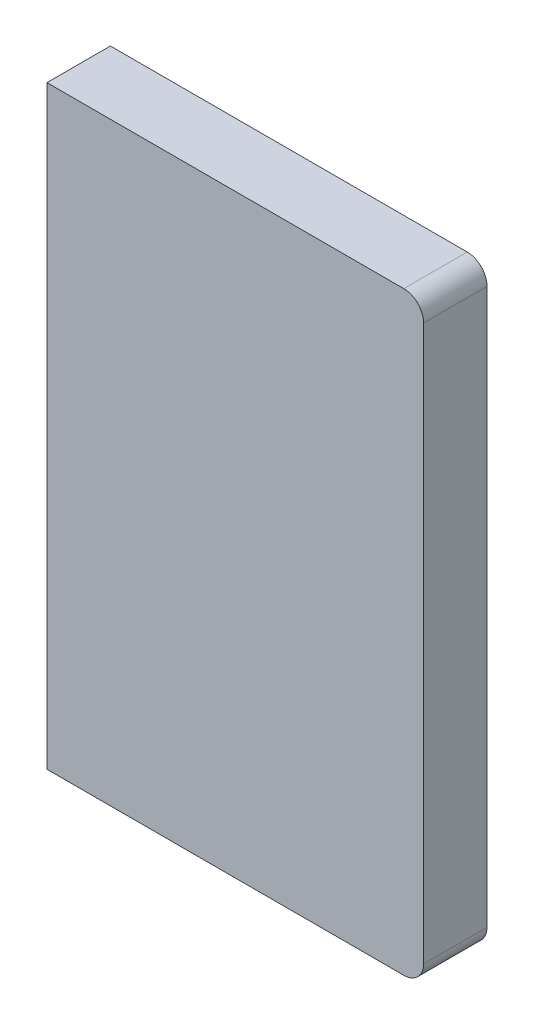
SolidWorks part; units mm, degrees
ref_plane "Front Plane" through (0, 0, 0) normal (0, 0, 1) x (1, 0, 0)
ref_plane "Top Plane" through (0, 0, 0) normal (0, 1, 0) x (1, 0, 0)
ref_plane "Right Plane" through (0, 0, 0) normal (1, 0, 0) x (0, 0, -1)
sketch "Sketch1" plane through (0, 0, 0) normal (0, 0, 1) x (1, 0, 0)
  line L1 (-24.0231, 103.7358) -> (70.9769, 103.7358)
  line L2 (-24.0231, 103.7358) -> (-24.0231, -46.2642)
  line L3 (-24.0231, -46.2642) -> (70.9769, -46.2642)
  line L4 (70.9769, 103.7358) -> (70.9769, -46.2642)
  dimension "D1" = 150
  dimension "D2" = 95
extrude "Boss-Extrude1" add sketch "Sketch1" along normal blind 16
fillet "Fillet1" radius 5 2 edges at (70.9769, -46.2642, 8) (70.9769, 103.7358, 8)
